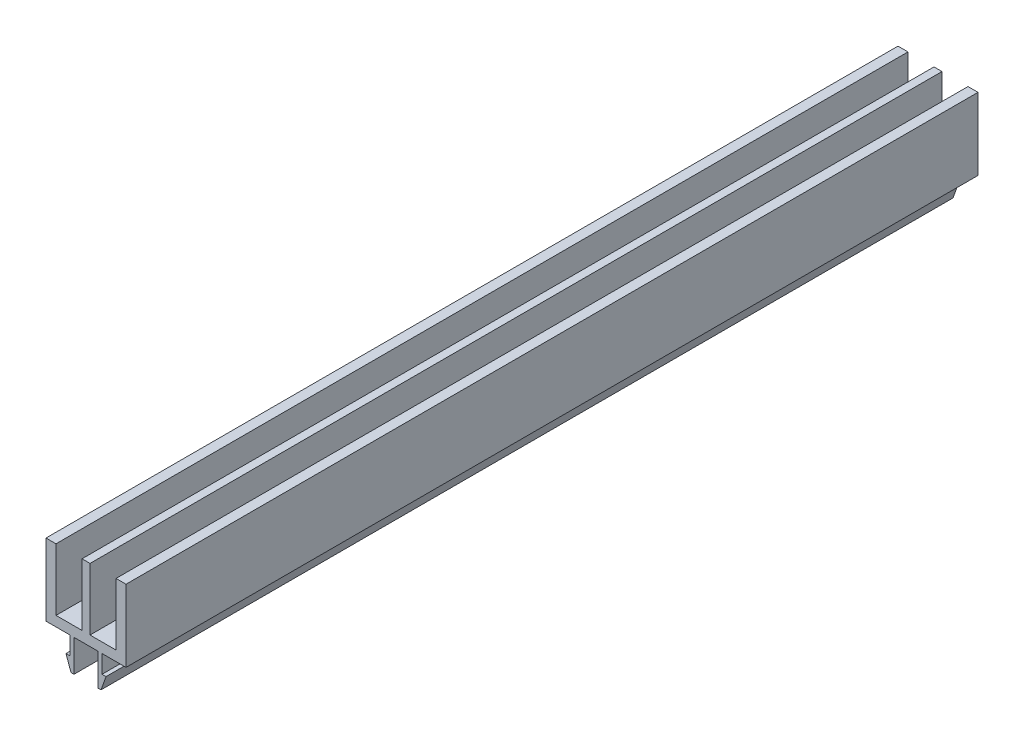
SolidWorks part; units mm, degrees
ref_plane "Plan de face" through (0, 0, 0) normal (0, 0, 1) x (1, 0, 0)
ref_plane "Plan de dessus" through (0, 0, 0) normal (0, 1, 0) x (1, 0, 0)
ref_plane "Plan de droite" through (0, 0, 0) normal (1, 0, 0) x (0, 0, -1)
ref_plane "Plan1" through (0, 0, 50) normal (0, 0, 1) x (1, 0, 0)
sketch "Esquisse1" plane through (0, 0, 50) normal (0, 0, 1) x (1, 0, 0)
  line L0 (-1, 2.5) -> (-7.5, 2.5)
  line L1 (-7.5, 2.5) -> (-7.5, 18)
  line L2 (-7.5, 18) -> (-10, 18)
  line L3 (-10, 18) -> (-10, 0)
  line L4 (-10, 0) -> (-4, 0)
  line L5 (-4, 0) -> (-4, -4.5)
  line L6 (-4, -4.5) -> (-5, -4.5)
  line L7 (-5, -4.5) -> (-3.75, -8)
  line L8 (-3.75, -8) -> (-3, -8)
  line L9 (-3, -8) -> (-3, 0)
  line L10 (-3, 0) -> (3, 0)
  line L11 (3, 0) -> (3, -8)
  line L12 (3, -8) -> (3.75, -8)
  line L13 (3.75, -8) -> (5, -4.5)
  line L14 (5, -4.5) -> (4, -4.5)
  line L15 (4, -4.5) -> (4, 0)
  line L16 (4, 0) -> (10, 0)
  line L17 (10, 0) -> (10, 18)
  line L18 (10, 18) -> (7.5, 18)
  line L19 (7.5, 18) -> (7.5, 2.5)
  line L20 (7.5, 2.5) -> (1, 2.5)
  line L21 (1, 2.5) -> (1, 18)
  line L22 (1, 18) -> (-1, 18)
  line L23 (-1, 18) -> (-1, 2.5)
extrude "Boss.-Extru.1" add sketch "Esquisse1" against normal blind 212.95
